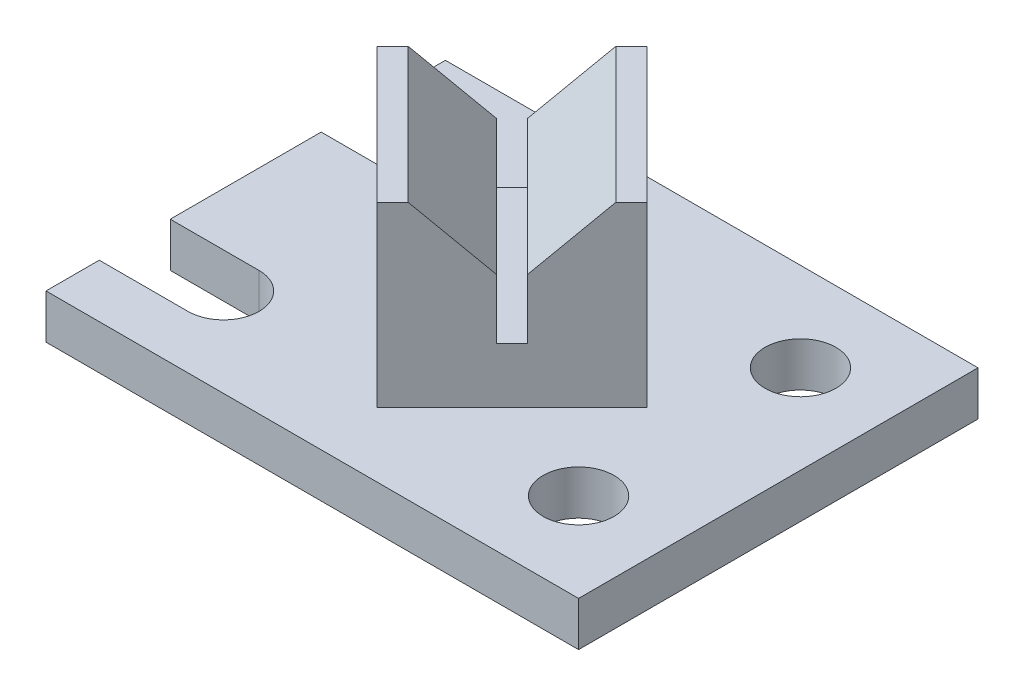
SolidWorks part; units mm, degrees
material "2014 Alloy"
ref_plane "Front Plane" through (0, 0, 0) normal (0, 0, 1) x (1, 0, 0)
ref_plane "Top Plane" through (0, 0, 0) normal (0, 1, 0) x (1, 0, 0)
ref_plane "Right Plane" through (0, 0, 0) normal (1, 0, 0) x (0, 0, -1)
sketch "Croquis1" plane through (0, 0, 0) normal (0, 1, 0) x (1, 0, 0)
  line L1 (-76.2, -57.15) -> (76.2, -57.15)
  line L2 (-76.2, -57.15) -> (-76.2, 57.15)
  line L3 (-76.2, 57.15) -> (76.2, 57.15)
  line L4 (76.2, -57.15) -> (76.2, 57.15)
  line L5 (-76.2, -57.15) -> (76.2, 57.15) construction
  line L6 (-76.2, 57.15) -> (76.2, -57.15) construction
  point P0 (0, 0)
  dimension "D1" = 152.4
  dimension "D2" = 114.3
extrude "Saliente-Extruir1" add sketch "Croquis1" along normal blind 12.7
sketch "Croquis2" plane through (0, 12.7, 0) normal (0, 1, 0) x (1, 0, 0)
  line L0 (76.2, -57.15) -> (76.2, 57.15) construction
  line L1 (-76.2, -57.15) -> (76.2, -57.15) construction
  line L2 (-76.2, 57.15) -> (-76.2, -57.15) construction
  line L3 (-76.2, -21.59) -> (-50.8, -21.59)
  line L4 (-76.2, -21.59) -> (-76.2, -41.91)
  line L5 (-76.2, -41.91) -> (-50.8, -41.91)
  line L6 (-50.8, -21.59) -> (-50.8, -41.91) construction
  line L7 (-76.2, -31.75) -> (-50.8, -31.75) construction
  circle A0 centre (50.8, -31.75) radius 10.16
  arc A1 (-50.8, -21.59) -> (-50.8, -41.91) centre (-50.8, -31.75) cw
  dimension "D3" = 20.32
  dimension "D1" = 25.4
  dimension "D2" = 25.4
  dimension "D4" = 20.32
  dimension "D5" = 25.4
  dimension "D6" = 25.4
extrude "Cortar-Extruir1" cut sketch "Croquis2" against normal through all
mirror "Simetría1" about plane through (0, 0, 0) normal (0, 0, 1) of "Cortar-Extruir1"
sketch "Croquis3" plane through (0, 12.7, 0) normal (0, 1, 0) x (1, 0, 0)
  line L1 (38.6705, 0) -> (0, -38.6705)
  line L2 (38.6705, 0) -> (0, 38.6705)
  line L3 (0, 38.6705) -> (-38.6705, 0)
  line L4 (0, -38.6705) -> (-38.6705, 0)
  line L5 (38.6705, 0) -> (-38.6705, 0) construction
  line L6 (0, 38.6705) -> (0, -38.6705) construction
  point P0 (0, 0)
extrude "Saliente-Extruir2" add sketch "Croquis3" along normal blind 50.8
sketch "Croquis4" plane through (19.3353, 0, 19.3353) normal (0.7071, 0, 0.7071) x (0.7071, 0, -0.7071)
  line L0 (0, 63.5) -> (0, 12.7) construction
  line L1 (-27.3442, 63.5) -> (27.3442, 63.5) construction
  line L2 (-27.3442, 12.7) -> (27.3442, 12.7) construction
  line L3 (-20.9942, 63.5) -> (20.9942, 63.5)
  line L4 (20.9942, 63.5) -> (3.175, 45.6808)
  line L5 (3.175, 45.6808) -> (3.175, 28.575)
  line L6 (3.175, 28.575) -> (-3.175, 28.575)
  line L7 (-3.175, 45.6808) -> (-3.175, 28.575)
  line L8 (-20.9942, 63.5) -> (-3.175, 45.6808)
  line L9 (-94.2927, 12.7) -> (13.4704, 12.7) construction
  line L10 (27.3442, 63.5) -> (27.3442, 12.7) construction
  point P9 (0, 63.5)
  point P13 (0, 28.575)
  dimension "D1" = 15.875
  dimension "D2" = 6.35
  dimension "D3" = 90
  dimension "D4" = 6.35
extrude "Cortar-Extruir2" cut sketch "Croquis4" against normal through all
